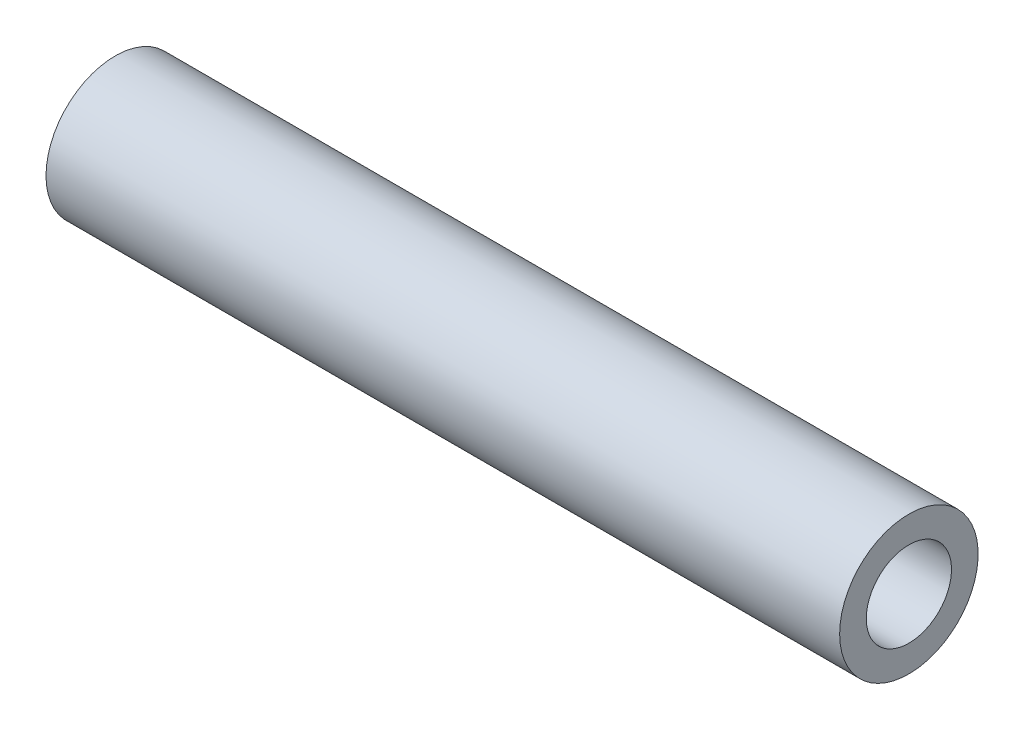
SolidWorks part; units mm, degrees
ref_plane "Front Plane" through (0, 0, 0) normal (0, 0, 1) x (1, 0, 0)
ref_plane "Top Plane" through (0, 0, 0) normal (0, 1, 0) x (1, 0, 0)
ref_plane "Right Plane" through (0, 0, 0) normal (1, 0, 0) x (0, 0, -1)
sketch "Sketch1" plane through (0, 0, 0) normal (0, 0, 1) x (1, 0, 0)
  line L0 (-101.3955, 0) -> (101.3955, 0) construction
  line L1 (-74.5, 8) -> (74.5, 8)
  line L2 (-74.5, 8) -> (-74.5, 13)
  line L3 (-74.5, 13) -> (74.5, 13)
  line L4 (74.5, 13) -> (74.5, 8)
  line L5 (0, 0) -> (0, 48.079) construction
  point P4 (0, 0)
  point P11 (0, 8)
  dimension "D1" = 202.7911
  dimension "D2" = 8
  dimension "D3" = 5
  dimension "D4" = 149
revolve "Revolve1" add sketch "Sketch1" angle 360 about L0
